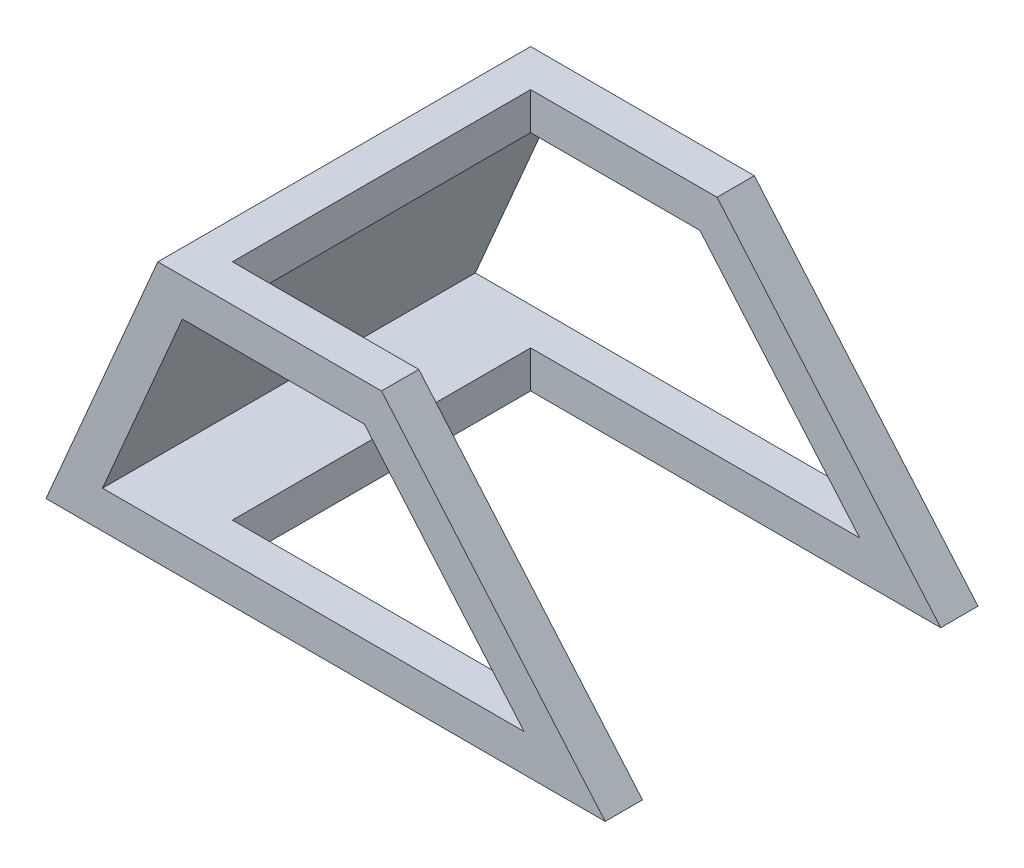
SolidWorks part; units mm, degrees
material "AISI 1020"
ref_plane "Front Plane" through (0, 0, 0) normal (0, 0, 1) x (1, 0, 0)
ref_plane "Top Plane" through (0, 0, 0) normal (0, 1, 0) x (1, 0, 0)
ref_plane "Right Plane" through (0, 0, 0) normal (1, 0, 0) x (0, 0, -1)
sketch "Sketch1" plane through (0, 0, 0) normal (0, 0, 1) x (1, 0, 0)
  line L0 (0, 0) -> (150, 0)
  line L1 (150, 0) -> (90, 70)
  line L2 (90, 70) -> (30, 70)
  line L3 (30, 70) -> (0, 0)
  line L4 (36.594, 60) -> (15.1654, 10)
  line L5 (15.1654, 10) -> (128.2578, 10)
  line L6 (128.2578, 10) -> (85.4007, 60)
  line L7 (85.4007, 60) -> (36.594, 60)
  dimension "D1" = 150
  dimension "D2" = 60
  dimension "D3" = 70
  dimension "D4" = 30
  dimension "D5" = 10
extrude "Boss-Extrude2" add sketch "Sketch1" along normal blind 100
sketch "Sketch10" plane through (0, 70, 0) normal (0, 1, 0) x (1, 0, 0)
  line L0 (150, -20) -> (50, -20)
  line L1 (150, -100) -> (150, 0) construction
  line L2 (50, -20) -> (50, -80)
  line L4 (50, -80) -> (150, -80)
  line L5 (150, 0) -> (90, 0) construction
  line L6 (150, -100) -> (90, -100) construction
  dimension "D1" = 60
  dimension "D2" = 20
  dimension "D3" = 20
extrude "Cut-Extrude-Thin5" cut sketch "Sketch10" against normal blind 100 and the other way through all thin
